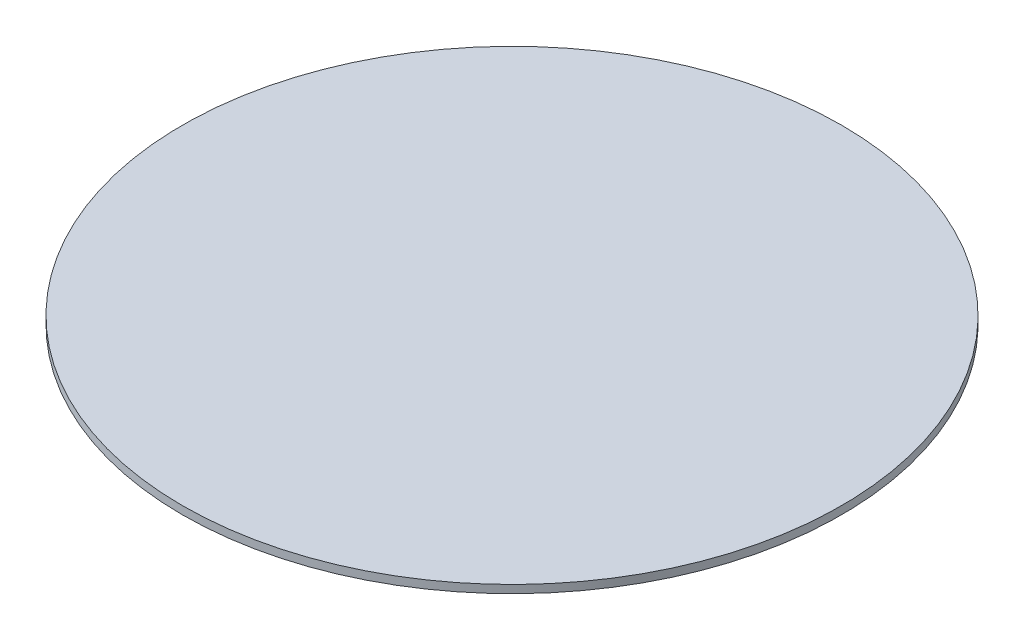
SolidWorks part; units mm, degrees
ref_plane "Front Plane" through (0, 0, 0) normal (0, 0, 1) x (1, 0, 0)
ref_plane "Top Plane" through (0, 0, 0) normal (0, 1, 0) x (1, 0, 0)
ref_plane "Right Plane" through (0, 0, 0) normal (1, 0, 0) x (0, 0, -1)
sketch "Sketch1" plane through (0, 0, 0) normal (0, 1, 0) x (1, 0, 0)
  line L0 (-57.7186, 100.5564) -> (-57.7186, 110.8764) construction
  line L5 (-77.8186, 100.5564) -> (-37.6186, 100.5564) construction
  line L6 (-77.8186, 100.5564) -> (-77.8186, 54.5564) construction
  line L7 (-77.8186, 54.5564) -> (-37.6186, 54.5564) construction
  line L8 (-37.6186, 100.5564) -> (-37.6186, 54.5564) construction
  line L9 (-77.8186, 100.5564) -> (-37.6186, 54.5564) construction
  line L14 (-77.8186, 54.5564) -> (-37.6186, 100.5564) construction
  line L15 (-57.7186, 110.8764) -> (-12.7186, 110.8764) construction
  line L16 (0, 0) -> (-57.7186, 110.8764) construction
  line L17 (0, 0) -> (0, 125) construction
  line L18 (0, 0) -> (57.7186, 110.8764) construction
  line L19 (57.7186, 110.8764) -> (12.7186, 110.8764) construction
  line L20 (77.8186, 54.5564) -> (37.6186, 100.5564) construction
  line L21 (77.8186, 100.5564) -> (37.6186, 54.5564) construction
  line L22 (37.6186, 100.5564) -> (37.6186, 54.5564) construction
  line L23 (77.8186, 54.5564) -> (37.6186, 54.5564) construction
  line L24 (77.8186, 100.5564) -> (77.8186, 54.5564) construction
  line L25 (77.8186, 100.5564) -> (37.6186, 100.5564) construction
  line L26 (57.7186, 100.5564) -> (57.7186, 110.8764) construction
  line L27 (115.9436, -0.2924) -> (124.881, -5.4524) construction
  line L28 (125.9936, 17.1147) -> (105.8936, -17.6995) construction
  line L29 (125.9936, 17.1147) -> (86.1565, 40.1147) construction
  line L30 (86.1565, 40.1147) -> (66.0565, 5.3005) construction
  line L31 (105.8936, -17.6995) -> (66.0565, 5.3005) construction
  line L32 (125.9936, 17.1147) -> (66.0565, 5.3005) construction
  line L33 (86.1565, 40.1147) -> (105.8936, -17.6995) construction
  line L34 (124.881, -5.4524) -> (102.381, -44.4236) construction
  line L35 (67.1625, -105.4239) -> (89.6625, -66.4528) construction
  line L36 (8.3379, -94.671) -> (68.2751, -82.8568) construction
  line L37 (48.1751, -117.671) -> (28.4379, -59.8568) construction
  line L38 (68.2751, -82.8568) -> (28.4379, -59.8568) construction
  line L39 (8.3379, -94.671) -> (28.4379, -59.8568) construction
  line L40 (48.1751, -117.671) -> (8.3379, -94.671) construction
  line L41 (48.1751, -117.671) -> (68.2751, -82.8568) construction
  line L42 (58.2251, -100.2639) -> (67.1625, -105.4239) construction
  line L43 (0, 0) -> (124.881, -5.4524) construction
  line L44 (0, 0) -> (67.1625, -105.4239) construction
  line L46 (-58.2251, -100.2639) -> (-67.1625, -105.4239) construction
  line L47 (-48.1751, -117.671) -> (-68.2751, -82.8568) construction
  line L48 (-48.1751, -117.671) -> (-8.3379, -94.671) construction
  line L49 (-8.3379, -94.671) -> (-28.4379, -59.8568) construction
  line L50 (-68.2751, -82.8568) -> (-28.4379, -59.8568) construction
  line L51 (-48.1751, -117.671) -> (-28.4379, -59.8568) construction
  line L52 (-8.3379, -94.671) -> (-68.2751, -82.8568) construction
  line L55 (-67.1625, -105.4239) -> (-89.6625, -66.4528) construction
  line L117 (-124.881, -5.4524) -> (-102.381, -44.4236) construction
  line L118 (-86.1565, 40.1147) -> (-105.8936, -17.6995) construction
  line L119 (-125.9936, 17.1147) -> (-66.0565, 5.3005) construction
  line L121 (-105.8936, -17.6995) -> (-66.0565, 5.3005) construction
  line L122 (-86.1565, 40.1147) -> (-66.0565, 5.3005) construction
  line L123 (-125.9936, 17.1147) -> (-86.1565, 40.1147) construction
  line L124 (-125.9936, 17.1147) -> (-105.8936, -17.6995) construction
  line L125 (-115.9436, -0.2924) -> (-124.881, -5.4524) construction
  line L126 (0, 0) -> (-67.1625, -105.4239) construction
  line L127 (0, 0) -> (-124.881, -5.4524) construction
  line L134 (-77.8186, 60.5564) -> (-37.6186, 60.5564) construction
  line L135 (37.6186, 60.5564) -> (77.8186, 60.5564) construction
  line L136 (91.3526, 37.1147) -> (71.2526, 2.3005) construction
  line L137 (33.6341, -62.8568) -> (13.5341, -97.671) construction
  line L138 (-13.5341, -97.671) -> (-33.6341, -62.8568) construction
  line L139 (-71.2526, 2.3005) -> (-91.3526, 37.1147) construction
  line L140 (-43.2186, 100.5564) -> (-43.2186, 54.5564) construction
  line L141 (-72.2186, 100.5564) -> (-72.2186, 54.5564) construction
  line L142 (72.2186, 100.5564) -> (72.2186, 54.5564) construction
  line L143 (43.2186, 100.5564) -> (43.2186, 54.5564) construction
  line L144 (123.1936, 12.2649) -> (83.3565, 35.2649) construction
  line L145 (108.6936, -12.8498) -> (68.8565, 10.1502) construction
  line L146 (65.4751, -87.7066) -> (25.6379, -64.7066) construction
  line L147 (50.9751, -112.8213) -> (11.1379, -89.8213) construction
  line L148 (-50.9751, -112.8213) -> (-11.1379, -89.8213) construction
  line L149 (-65.4751, -87.7066) -> (-25.6379, -64.7066) construction
  line L150 (-108.6936, -12.8498) -> (-68.8565, 10.1502) construction
  line L151 (-123.1936, 12.2649) -> (-83.3565, 35.2649) construction
  line L152 (-77.8186, 94.5564) -> (-37.6186, 94.5564) construction
  line L153 (37.6186, 94.5564) -> (77.8186, 94.5564) construction
  line L154 (120.7975, 20.1147) -> (100.6975, -14.6995) construction
  line L155 (63.0789, -79.8568) -> (42.9789, -114.671) construction
  line L156 (-42.9789, -114.671) -> (-63.0789, -79.8568) construction
  line L157 (-100.6975, -14.6995) -> (-120.7975, 20.1147) construction
  circle A5 centre (0, 0) radius 125 construction
  circle A7 centre (0, 0) radius 206.3172
  point P3 (-57.7186, 77.5564)
  point P20 (57.7186, 77.5564)
  point P24 (96.0251, 11.2076)
  point P40 (38.3065, -88.7639)
  point P41 (-38.3065, -88.7639)
  point P57 (-96.0251, 11.2076)
  point P58 (0, 0)
  point P69 (0, 0)
  point P94 (0, 0)
  point P107 (0, 0)
  dimension "D1" = 40.2
  dimension "D6" = 250
  dimension "D11" = 6
  dimension "D2" = 46
  dimension "D3" = 10.32
  dimension "D4" = 45
  dimension "D5" = 55
  dimension "D8" = 6
  dimension "D9" = 5.6
  dimension "D7" = 3
  dimension "D10" = 5.6
extrude "Boss-Extrude1" add sketch "Sketch1" along normal blind 5
